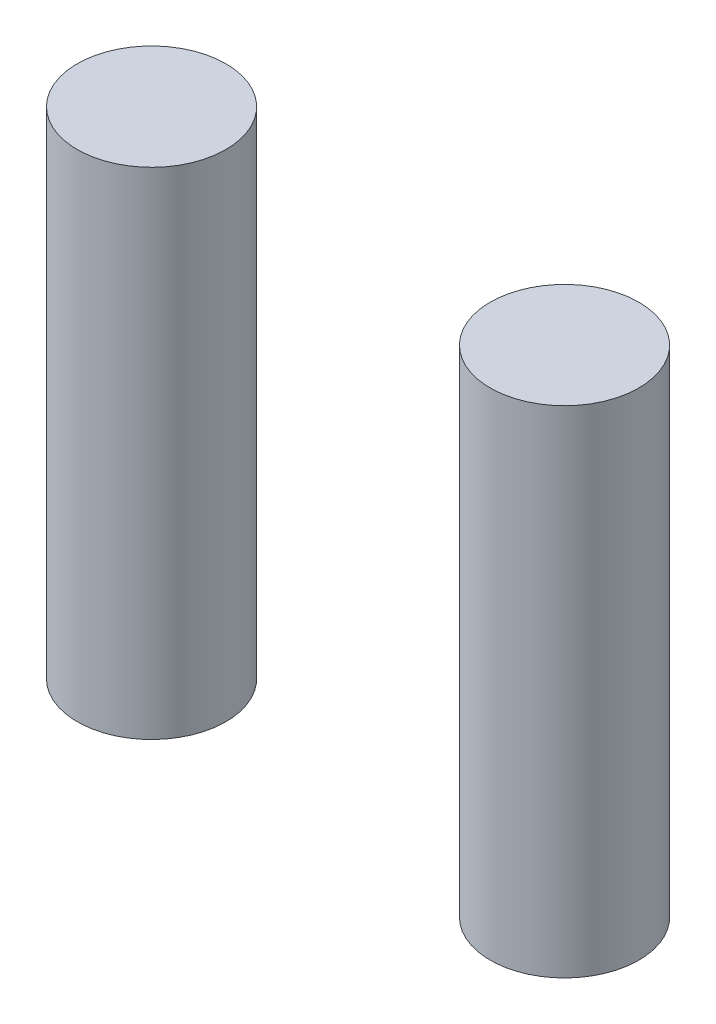
SolidWorks part; units mm, degrees
material "AISI 1020 Steel, Cold Rolled"
ref_plane "Front Plane" through (0, 0, 0) normal (0, 0, 1) x (1, 0, 0)
ref_plane "Top Plane" through (0, 0, 0) normal (0, 1, 0) x (1, 0, 0)
ref_plane "Right Plane" through (0, 0, 0) normal (1, 0, 0) x (0, 0, -1)
sketch "Sketch1" plane through (0, 0, 0) normal (0, 1, 0) x (1, 0, 0)
  circle A0 centre (0, 0) radius 1.143
  circle A1 centre (6.35, 0) radius 1.143
  point P5 (0, 0)
  dimension "D1" = 6.35
  dimension "D2" = 2.286
extrude "Boss-Extrude1" add sketch "Sketch1" along normal blind 7.62
